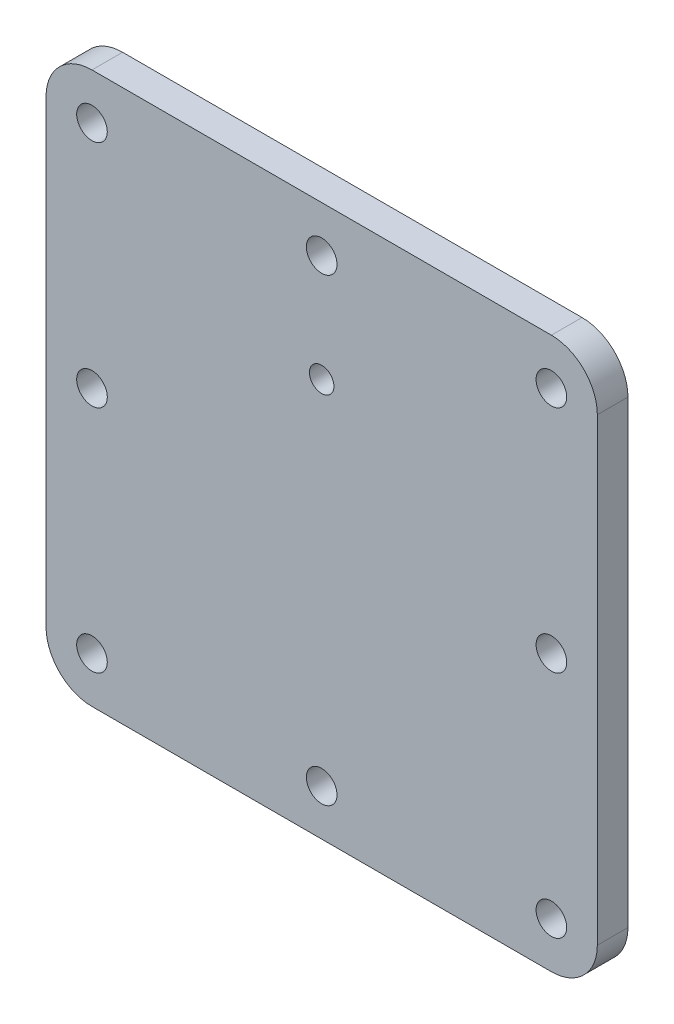
SolidWorks part; units mm, degrees
ref_plane "Front Plane" through (0, 0, 0) normal (0, 0, 1) x (1, 0, 0)
ref_plane "Top Plane" through (0, 0, 0) normal (0, 1, 0) x (1, 0, 0)
ref_plane "Right Plane" through (0, 0, 0) normal (1, 0, 0) x (0, 0, -1)
sketch "Sketch2" plane through (0, 0, 0) normal (0, 0, 1) x (1, 0, 0)
  line L0 (-75, 75) -> (75, 75) construction
  line L1 (-75, 90) -> (75, 90)
  line L2 (-90, 75) -> (-90, -75)
  line L3 (-75, -90) -> (75, -90)
  line L4 (90, 75) -> (90, -75)
  line L5 (-90, 90) -> (90, -90) construction
  line L6 (-90, -90) -> (90, 90) construction
  line L7 (75, 75) -> (75, -75) construction
  line L8 (75, -75) -> (-75, -75) construction
  line L9 (-75, -75) -> (-75, 75) construction
  line L15 (-60, 60) -> (60, -60) construction
  line L16 (-60, -60) -> (60, 60) construction
  arc A0 (-90, -75) -> (-75, -90) centre (-75, -75) ccw
  arc A1 (75, -90) -> (90, -75) centre (75, -75) ccw
  arc A2 (75, 90) -> (90, 75) centre (75, 75) cw
  arc A3 (-75, 90) -> (-90, 75) centre (-75, 75) ccw
  circle A4 centre (-75, 75) radius 5
  circle A5 centre (0, 75) radius 5
  circle A6 centre (75, 75) radius 5
  circle A7 centre (-75, 0) radius 5
  circle A8 centre (0, 0) radius 5 construction
  circle A9 centre (75, 0) radius 5
  circle A10 centre (-75, -75) radius 5
  circle A11 centre (0, -75) radius 5
  circle A12 centre (75, -75) radius 5
  point P0 (0, 0)
  dimension "D3" = 15
  dimension "D4" = 10
  dimension "D1" = 180
  dimension "D2" = 180
  dimension "D8" = 120
  dimension "D7" = 3
extrude "Boss-Extrude1" add sketch "Sketch2" along normal blind 10
sketch "Sketch3" plane through (0, 0, 10) normal (0, 0, 1) x (1, 0, 0)
  line L1 (-50, 50) -> (50, 50) construction
  line L2 (-50, 50) -> (-50, -50) construction
  line L3 (-50, -50) -> (50, -50) construction
  line L4 (50, 50) -> (50, -50) construction
  line L5 (-50, 50) -> (50, -50) construction
  line L6 (-50, -50) -> (50, 50) construction
  line L7 (0, 0) -> (-40, 0) construction
  line L8 (0, 0) -> (0, 40) construction
  line L9 (0, 40) -> (-40, 40) construction
  line L10 (-40, 0) -> (-40, 40) construction
  circle A0 centre (0, 0) radius 4 construction
  point P0 (0, 0)
  dimension "D5" = 8
  dimension "D1" = 100
  dimension "D2" = 100
  dimension "D3" = 40
  dimension "D4" = 40
sketch "Sketch5" plane through (0, 0, 10) normal (0, 0, 1) x (1, 0, 0)
  circle A0 centre (0, 40) radius 4
  dimension "D1" = 8
extrude "Cut-Extrude2" cut sketch "Sketch5" against normal blind 10
